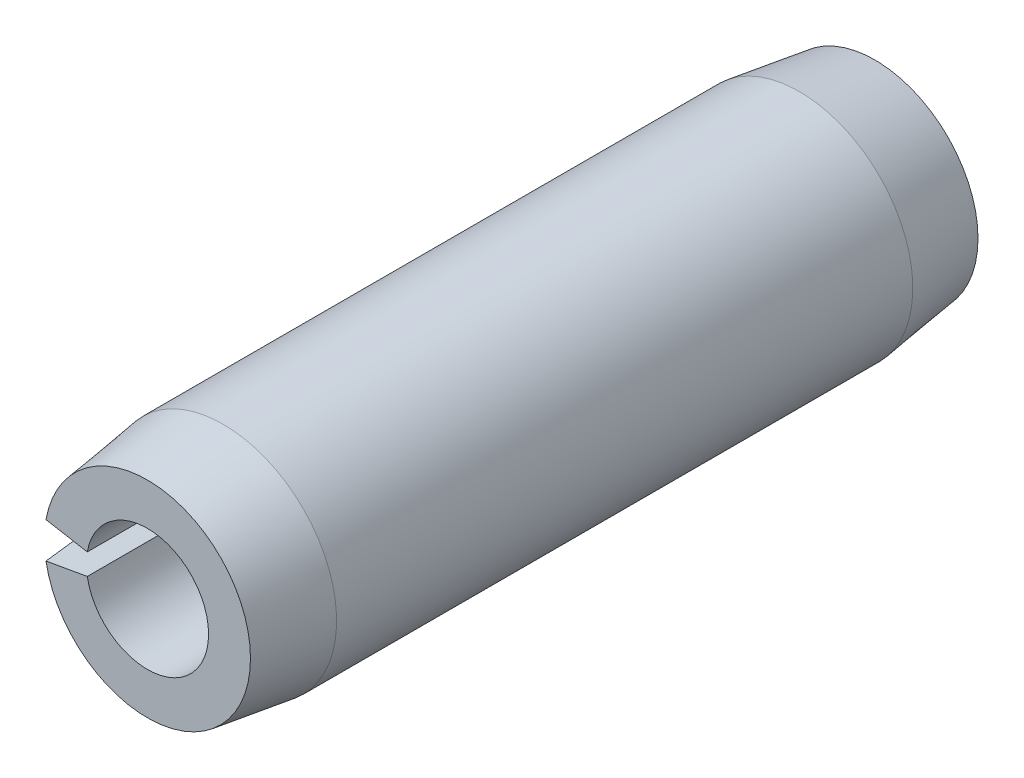
SolidWorks part; units mm, degrees
ref_plane "Front Plane" through (0, 0, 0) normal (0, 0, 1) x (1, 0, 0)
ref_plane "Top Plane" through (0, 0, 0) normal (0, 1, 0) x (1, 0, 0)
ref_plane "Right Plane" through (0, 0, 0) normal (1, 0, 0) x (0, 0, -1)
sketch "Sketch5" plane through (0, 0, 0) normal (0, 0, 1) x (1, 0, 0)
  line L0 (0.5334, 0) -> (0.9906, 0) construction
  line L1 (-0.9756, 0.172) -> (-0.5253, 0.0926)
  line L2 (-0.5253, -0.0926) -> (-0.9756, -0.172)
  arc A0 (-0.9756, -0.172) -> (-0.9756, 0.172) centre (0, 0) ccw
  arc A1 (-0.5253, -0.0926) -> (-0.5253, 0.0926) centre (0, 0) ccw
  circle A2 centre (0, 0) radius 0.9906 construction
  dimension "Diameter" = 1.9812
  dimension "Wall Thickness" = 0.4572
  dimension "Opening Angle" = 20
sketch "Sketch6" plane through (0, 0, 0) normal (1, 0, 0) x (0, 0, -1)
  line L0 (3.175, 0) -> (-3.175, 0) construction
  line L1 (0, 0.9906) -> (0, -0.9906) construction
  line L4 (0, 0.9906) -> (0, -0.9906) construction
  line L5 (3.175, 0) -> (3.175, 0.9906) construction
  line L6 (3.175, 0.9906) -> (-3.175, 0.9906) construction
  line L7 (-3.175, 0.9906) -> (-3.175, 0) construction
  line L8 (3.175, 0.8992) -> (2.5146, 0.9906)
  dimension "Length" = 6.35
  dimension "Chamfer" = 0.6604
  dimension "D1" = 0.0914
sketch "Sketch1" plane through (0, 0, 0) normal (0, 0, 1) x (1, 0, 0)
  line L1 (-0.5253, -0.0926) -> (-0.9756, -0.172) construction
  line L2 (-0.9756, 0.172) -> (-0.5253, 0.0926) construction
  line L3 (-0.5253, -0.0926) -> (-0.9756, -0.172)
  line L4 (-0.9756, 0.172) -> (-0.5253, 0.0926)
  arc A2 (-0.9756, -0.172) -> (-0.9756, 0.172) centre (0, 0) ccw construction
  arc A3 (-0.5253, -0.0926) -> (-0.5253, 0.0926) centre (0, 0) ccw construction
  arc A4 (-0.9756, -0.172) -> (-0.9756, 0.172) centre (0, 0) ccw
  arc A5 (-0.5253, -0.0926) -> (-0.5253, 0.0926) centre (0, 0) ccw
extrude "Extrude1" add sketch "Sketch1" against normal up to vertex (3.175 mm away) and the other way up to vertex (3.175 mm away) up to point (0, 0.9906, -3.175) other way up to point (0, 0.9906, 3.175)
sketch "Sketch2" plane through (0, 0, 0) normal (1, 0, 0) x (0, 0, -1)
  line L0 (3.175, 0.8992) -> (2.5146, 0.9906)
  line L1 (2.5146, 0.9906) -> (3.175, 0.9906)
  line L4 (3.175, 0.9906) -> (3.175, 0.8992)
revolve "Cut-Revolve1" cut sketch "Sketch2" angle 360 about L0
mirror "Mirror1" about plane through (0, 0, 0) normal (0, 0, 1) of "Cut-Revolve1"
equation "\"D1@Sketch6\"=\"Wall Thickness@Sketch5\"*.2"
equation "\"Chamfer@Sketch6\"=\"Diameter@Sketch5\"/3"
